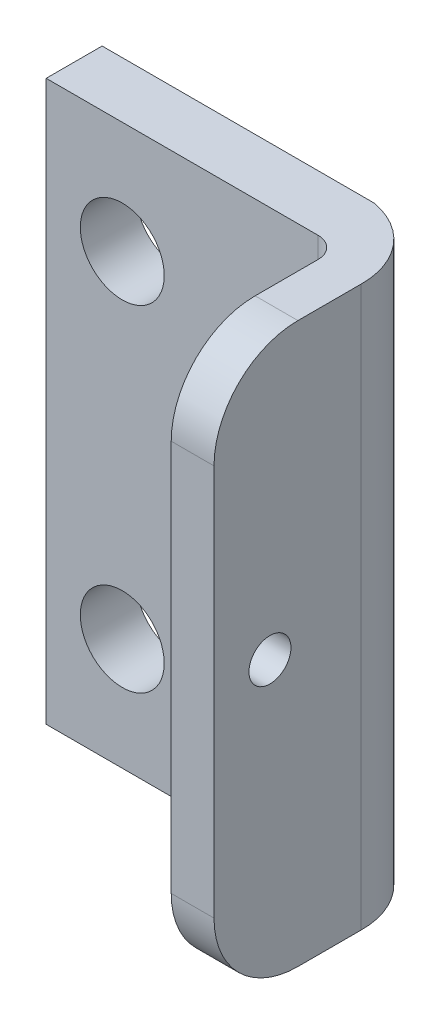
SolidWorks part; units mm, degrees
ref_plane "Front Plane" through (0, 0, 0) normal (0, 0, 1) x (1, 0, 0)
ref_plane "Top Plane" through (0, 0, 0) normal (0, 1, 0) x (1, 0, 0)
ref_plane "Right Plane" through (0, 0, 0) normal (1, 0, 0) x (0, 0, -1)
sketch "Sketch1" plane through (0, 0, 0) normal (0, 0, 1) x (1, 0, 0)
  line L1 (0, 0) -> (9.72, 0)
  line L2 (0, 0) -> (0, 20)
  line L3 (0, 20) -> (9.72, 20)
  line L4 (9.72, 0) -> (9.72, 20)
  line L5 (4.86, 20) -> (4.86, 0) construction
  line L6 (0, 10) -> (9.72, 10) construction
  circle A0 centre (2.72, 16) radius 1.5
  circle A1 centre (2.72, 4) radius 1.5
  point P380 (4.86, 10)
  dimension "D2" = 3
  dimension "D3" = 3
  dimension "D1" = 20
  dimension "D4" = 4
  dimension "D5" = 4
  dimension "D6" = 2.72
  dimension "D7" = 7
extrude "Boss-Extrude1" add sketch "Sketch1" along normal blind 2
sketch "Sketch2" plane through (0, 0, 0) normal (0, -1, 0) x (1, 0, 0)
  line L0 (9.72, 2) -> (9.72, 0)
  line L1 (11.9997, 2.75) -> (10.47, 2.75)
  line L2 (0, 2) -> (9.72, 2) construction
  arc A0 (9.72, 0) -> (11.9997, 2.75) centre (9.25, 2.7095) ccw
  arc A2 (9.72, 2) -> (10.47, 2.75) centre (9.72, 2.75) ccw
  dimension "D1" = 5.5
  dimension "D3" = 1.5
  dimension "D2" = 0.47
  dimension "D4" = 0.75
  dimension "D5" = 0.75
extrude "Boss-Extrude2" add sketch "Sketch2" against normal blind 20
ref_plane "Plane1" through (12, 0, 0) normal (1, 0, 0) x (0, 0, -1)
sketch "Sketch3" plane through (12, 0, 0) normal (1, 0, 0) x (0, 0, -1)
  line L0 (-2.75, 20) -> (-5, 20)
  line L1 (-8, 17) -> (-8, 3)
  line L2 (-5, 0) -> (-2.75, 0)
  line L3 (-2.75, 20) -> (-2.75, 0)
  line L4 (0, 0) -> (0, 20) construction
  arc A0 (-8, 3) -> (-5, 0) centre (-5, 3) ccw
  arc A1 (-5, 20) -> (-8, 17) centre (-5, 17) ccw
  circle A2 centre (-6, 10) radius 0.75
  dimension "D2" = 3
  dimension "D3" = 1.5
  dimension "D1" = 8
  dimension "D4" = 2
  dimension "D5" = 10
extrude "Boss-Extrude3" add sketch "Sketch3" against normal up to vertex (1.53 mm away)
